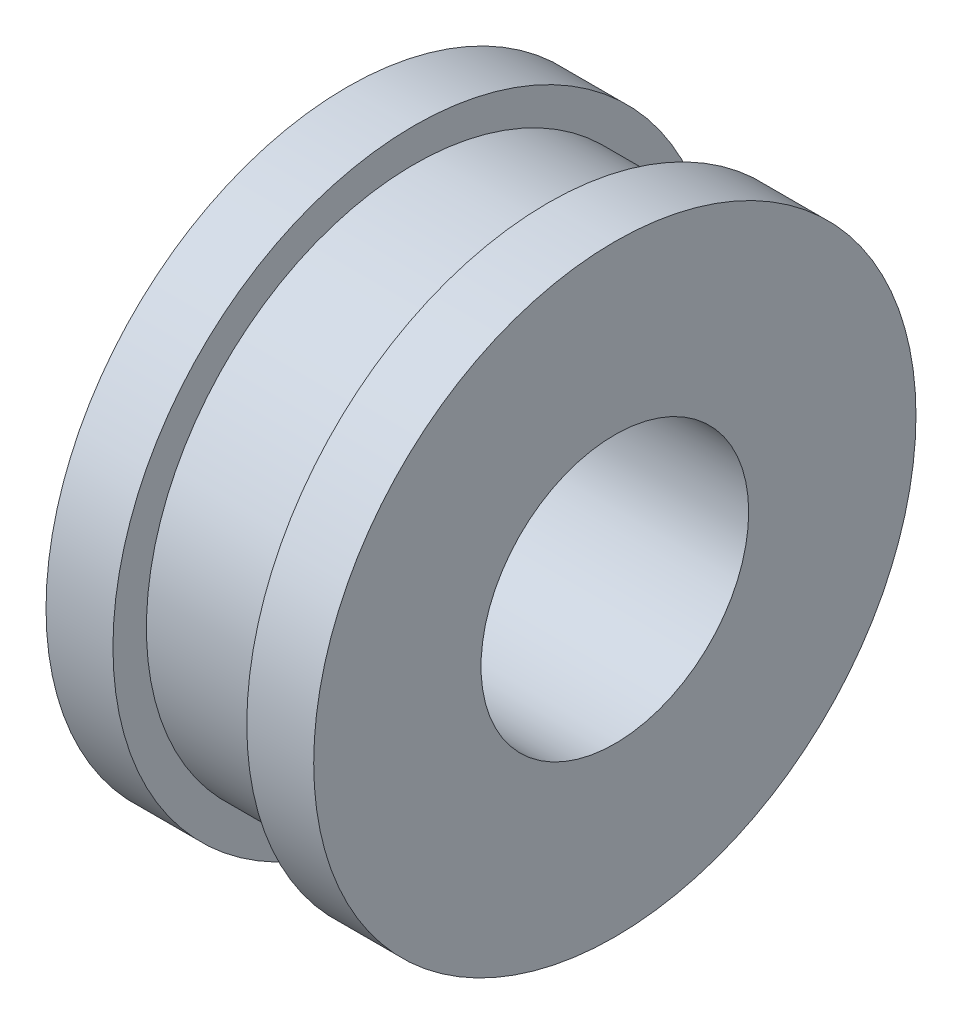
SolidWorks part; units mm, degrees
ref_plane "Front Plane" through (0, 0, 0) normal (0, 0, 1) x (1, 0, 0)
ref_plane "Top Plane" through (0, 0, 0) normal (0, 1, 0) x (1, 0, 0)
ref_plane "Right Plane" through (0, 0, 0) normal (1, 0, 0) x (0, 0, -1)
sketch "Sketch2" plane through (0, 0, 0) normal (0, 0, 1) x (1, 0, 0)
  line L0 (0, 0) -> (-10.2913, 0) construction
  line L1 (-6, 4) -> (2, 4)
  line L3 (-6, 4) -> (-6, 9)
  line L4 (-6, 9) -> (-4, 9)
  line L5 (-4, 9) -> (-4, 8)
  line L6 (-4, 8) -> (0, 8)
  line L7 (0, 8) -> (0, 9)
  line L8 (0, 9) -> (2, 9)
  line L10 (2, 9) -> (2, 4)
  dimension "D1" = 8
  dimension "D2" = 4
  dimension "D3" = 2
  dimension "D4" = 2
  dimension "D5" = 1
  dimension "D6" = 5
  dimension "D7" = 5
revolve "Revolve1" add sketch "Sketch2" angle 360 about L0
